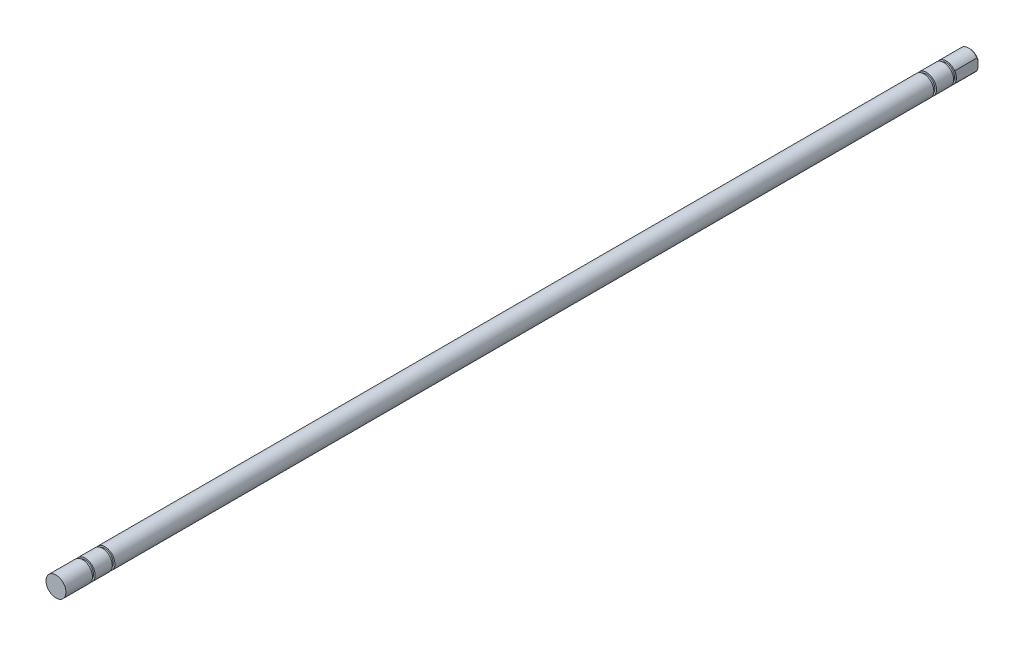
SolidWorks part; units mm, degrees
material "AISI 4340 Steel, normalized"
ref_plane "Front Plane" through (0, 0, 0) normal (0, 0, 1) x (1, 0, 0)
ref_plane "Top Plane" through (0, 0, 0) normal (0, 1, 0) x (1, 0, 0)
ref_plane "Right Plane" through (0, 0, 0) normal (1, 0, 0) x (0, 0, -1)
sketch "Sketch1" plane through (0, 0, 0) normal (0, 0, 1) x (1, 0, 0)
  circle A0 centre (0, 0) radius 3
extrude "Boss-Extrude1" add sketch "Sketch1" along normal blind 275
sketch "Sketch3" plane through (0, 0, 0) normal (1, 0, 0) x (0, 0, -1)
  line L0 (0, 3) -> (-275, 3) construction
  line L1 (-267, 3) -> (-266.2, 3)
  line L2 (-267, 3) -> (-267, 2.5)
  line L3 (-267, 2.5) -> (-266.2, 2.5)
  line L4 (-266.2, 3) -> (-266.2, 2.5)
  line L5 (-275, 3) -> (-275, -3) construction
  line L6 (-263.365, 0) -> (-260, 0) construction
  line L7 (-261.05, 3) -> (-260.25, 3)
  line L8 (-261.05, 3) -> (-261.05, 2.5)
  line L9 (-261.05, 2.5) -> (-260.25, 2.5)
  line L10 (-260.25, 3) -> (-260.25, 2.5)
  line L11 (-13.8, 3) -> (-13, 3)
  line L12 (-13.8, 3) -> (-13.8, 2.5)
  line L13 (-13.8, 2.5) -> (-13, 2.5)
  line L14 (-13, 3) -> (-13, 2.5)
  line L15 (-7.85, 3) -> (-7.05, 3)
  line L16 (-7.85, 3) -> (-7.85, 2.5)
  line L17 (-7.85, 2.5) -> (-7.05, 2.5)
  line L18 (-7.05, 3) -> (-7.05, 2.5)
  point P12 (-260.65, 2.5)
  point P21 (-7.05, 2.75)
  dimension "D1" = 0.8
  dimension "D2" = 0.5
  dimension "D3" = 8
  dimension "D4" = 0.5
  dimension "D5" = 0.8
  dimension "D6" = 13.95
  dimension "D7" = 5.15
  dimension "D8" = 0.5
  dimension "D9" = 0.8
  dimension "D10" = 0.5
  dimension "D11" = 0.8
  dimension "D12" = 5.15
  dimension "D13" = 261.2
revolve "Cut-Revolve1" cut sketch "Sketch3" angle 360 about L6
sketch "Sketch4" plane through (0, 0, 0) normal (0, 1, 0) x (1, 0, 0)
  line L0 (0, 6.9099) -> (0, -272.7358) construction
  line L1 (3, 0) -> (-3, 0) construction
  line L2 (2.5, 0) -> (5.9701, 0)
  line L3 (2.5, 0) -> (2.5, -7)
  line L4 (2.5, -7) -> (5.9701, -7)
  line L5 (5.9701, 0) -> (5.9701, -7)
  line L6 (-5.4253, 0) -> (-2.5, 0)
  line L7 (-5.4253, 0) -> (-5.4253, -7)
  line L8 (-5.4253, -7) -> (-2.5, -7)
  line L9 (-2.5, 0) -> (-2.5, -7)
  line L10 (3, -7.05) -> (3, 0) construction
  line L11 (-3, 0) -> (-3, -7.05) construction
  dimension "D1" = 7
  dimension "D2" = 0.5
  dimension "D3" = 0.5
extrude "Cut-Extrude2" cut sketch "Sketch4" against normal through all both and the other way through all
chamfer "Chamfer1" distance 0.3 angle 45 2 edges at (0, -3, 0) (0, 3, 0)
